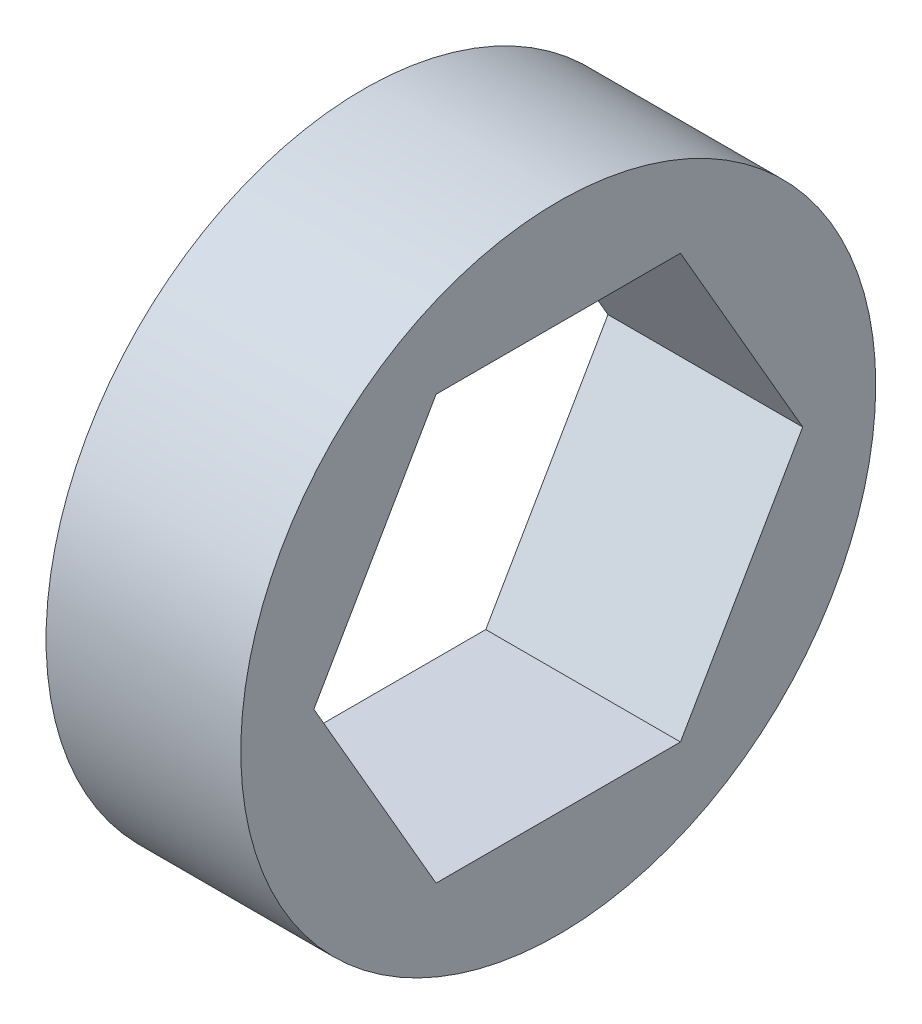
SolidWorks part; units mm, degrees
material "PET"
ref_plane "Front" through (0, 0, 0) normal (0, 0, 1) x (1, 0, 0)
ref_plane "Top" through (0, 0, 0) normal (0, 1, 0) x (1, 0, 0)
ref_plane "Right" through (0, 0, 0) normal (1, 0, 0) x (0, 0, -1)
sketch "Sketch1" plane through (0, 0, 0) normal (1, 0, 0) x (0, 0, -1)
  line L1 (7.3323, 0) -> (3.6662, 6.35)
  line L2 (3.6662, 6.35) -> (-3.6662, 6.35)
  line L3 (-3.6662, 6.35) -> (-7.3323, 0)
  line L4 (-7.3323, 0) -> (-3.6662, -6.35)
  line L5 (-3.6662, -6.35) -> (3.6662, -6.35)
  line L6 (3.6662, -6.35) -> (7.3323, 0)
  circle A0 centre (0, 0) radius 9.525
  circle A1 centre (0, 0) radius 6.35 construction
  dimension "D2" = 19.05
  dimension "D1" = 12.7
extrude "Boss-Extrude1" add sketch "Sketch1" along normal blind 5.842
